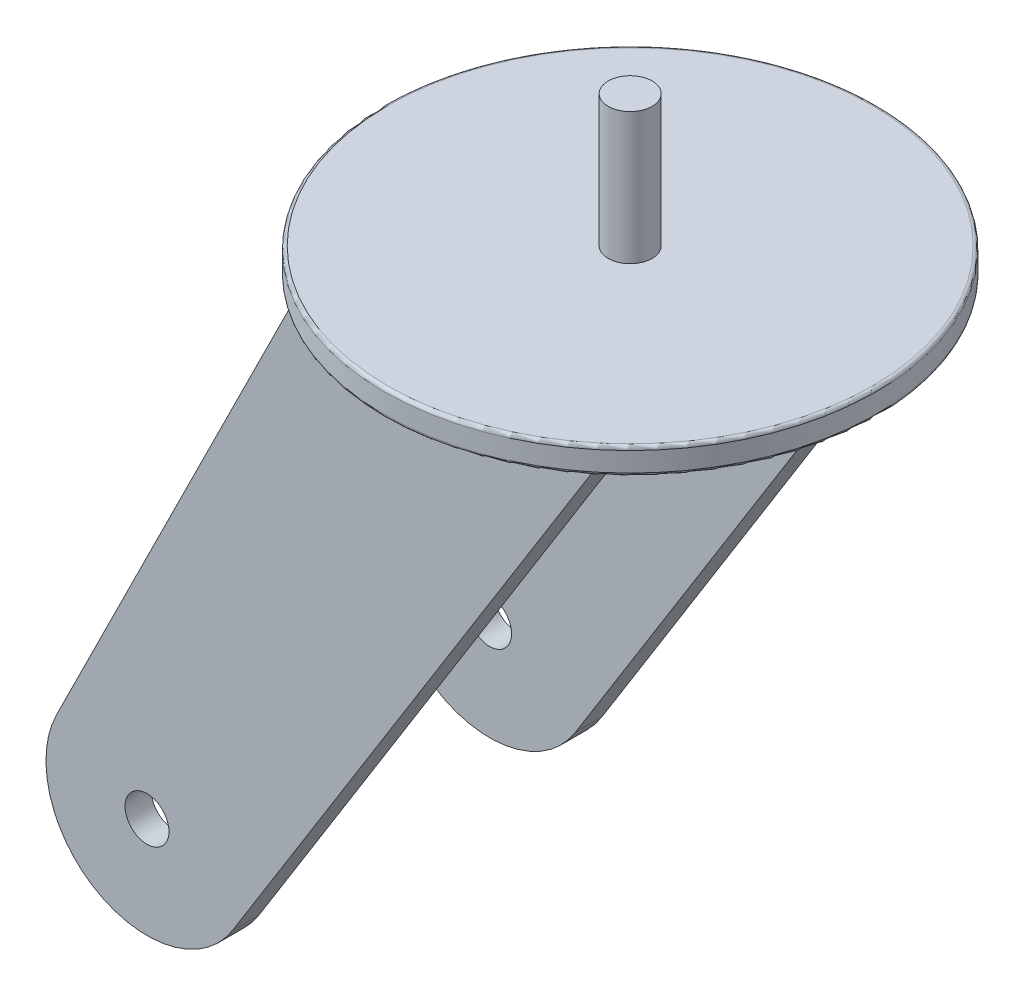
SolidWorks part; units mm, degrees
ref_plane "Front Plane" through (0, 0, 0) normal (0, 0, 1) x (1, 0, 0)
ref_plane "Top Plane" through (0, 0, 0) normal (0, 1, 0) x (1, 0, 0)
ref_plane "Right Plane" through (0, 0, 0) normal (1, 0, 0) x (0, 0, -1)
sketch "Sketch1" plane through (0, 0, 0) normal (0, 1, 0) x (1, 0, 0)
  circle A0 centre (0, 0) radius 71.12
  dimension "D1" = 142.24
extrude "Boss-Extrude1" add sketch "Sketch1" along normal blind 7.62
fillet "Fillet1" radius 0.9906 2 edges at (0, 7.62, 71.12) (0, 0, 71.12)
ref_plane "Plane1" through (0, 0, 45.72) normal (0, 0, 1) x (1, 0, 0)
sketch "Sketch3" plane through (0, 0, 45.72) normal (0, 0, 1) x (1, 0, 0)
  line L0 (0, 0) -> (43.18, 0)
  line L1 (-70.1294, 0) -> (70.1294, 0) construction
  line L2 (0, 0) -> (-43.18, 0)
  line L3 (43.18, 0) -> (-61.5796, -167.8647)
  line L4 (-43.18, 0) -> (-112.5134, -139.3913)
  arc A0 (-112.5134, -139.3913) -> (-61.5796, -167.8647) centre (-86.36, -152.4) ccw
  circle A1 centre (-86.36, -152.4) radius 6.35
  dimension "D3" = 58.42
  dimension "D4" = 152.4
  dimension "D5" = 129.54
  dimension "D6" = 12.7
  dimension "D1" = 43.18
  dimension "D2" = 43.18
extrude "Boss-Extrude2" add sketch "Sketch3" along normal blind 7.62
mirror "Mirror1" about plane through (0, 0, 0) normal (0, 0, 1) of "Boss-Extrude2"
sketch "Sketch5" plane through (0, 7.62, 0) normal (0, 1, 0) x (1, 0, 0)
  circle A0 centre (0, 0) radius 6.35
  dimension "D1" = 12.7
extrude "Boss-Extrude3" add sketch "Sketch5" along normal blind 38.1
